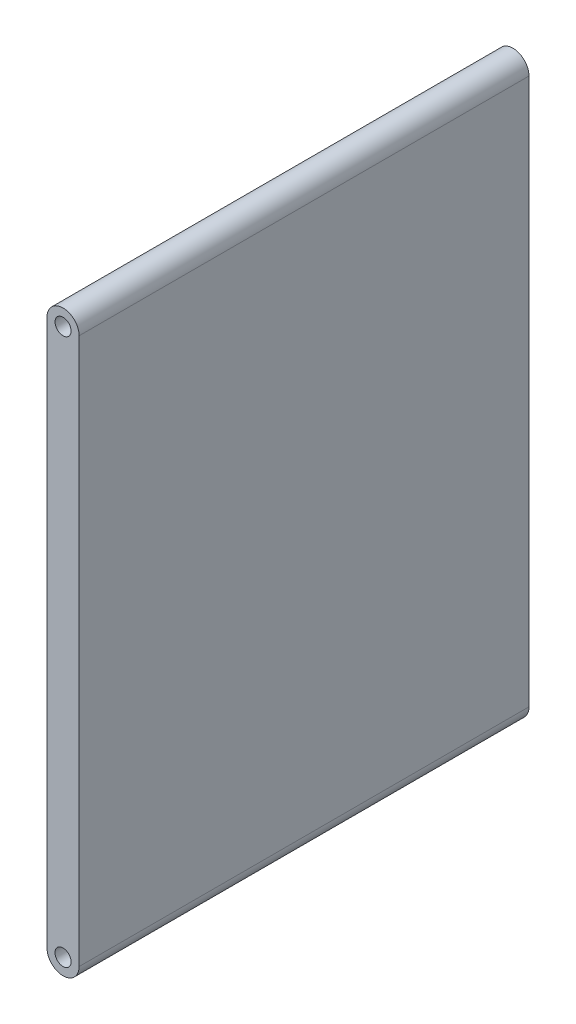
SolidWorks part; units mm, degrees
ref_plane "Спереди" through (0, 0, 0) normal (0, 0, 1) x (1, 0, 0)
ref_plane "Сверху" through (0, 0, 0) normal (0, 1, 0) x (1, 0, 0)
ref_plane "Справа" through (0, 0, 0) normal (1, 0, 0) x (0, 0, -1)
sketch "Эскиз1" plane through (0, 0, 0) normal (0, 0, 1) x (1, 0, 0)
  line L0 (50, 0) -> (-50, 0) construction
  line L1 (0, -50) -> (0, 50) construction
  line L2 (0, 17) -> (0, -17)
  line L3 (0, 0) -> (2, 0) construction
  line L4 (2, 17) -> (2, -17)
  circle A0 centre (1, 17) radius 0.5
  arc A1 (0, 17) -> (2, 17) centre (1, 17) cw
  arc A2 (0, -17) -> (2, -17) centre (1, -17) ccw
  circle A3 centre (1, -17) radius 0.5
  dimension "D3" = 1
  dimension "D1" = 2
  dimension "D2" = 17
extrude "Бобышка-Вытянуть1" add sketch "Эскиз1" along normal blind 28 contours L4 A2 L2 A1 | A0 | A3
